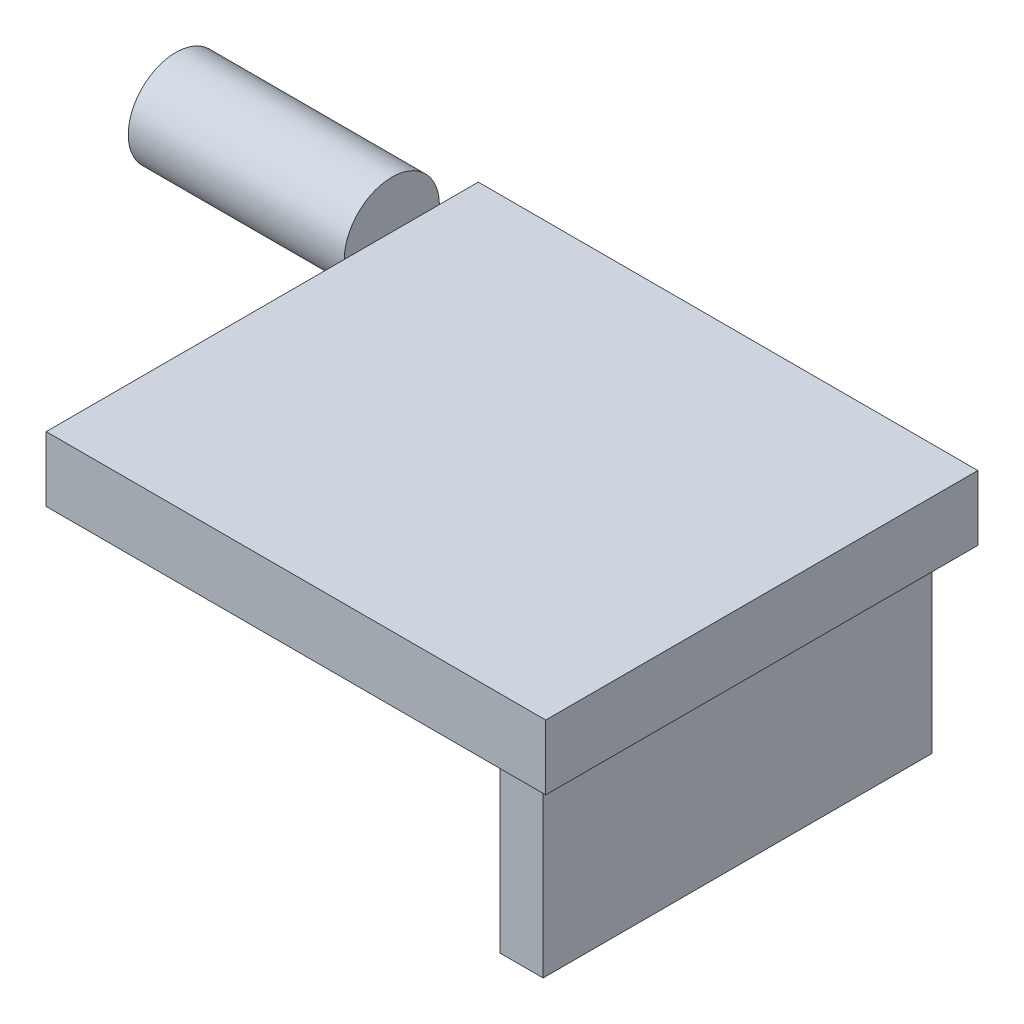
SolidWorks part; units mm, degrees
ref_plane "Front Plane" through (0, 0, 0) normal (0, 0, 1) x (1, 0, 0)
ref_plane "Top Plane" through (0, 0, 0) normal (0, 1, 0) x (1, 0, 0)
ref_plane "Right Plane" through (0, 0, 0) normal (1, 0, 0) x (0, 0, -1)
sketch "Sketch1" plane through (0, 0, 0) normal (0, 1, 0) x (1, 0, 0)
  line L1 (0, 0) -> (29.3624, 0)
  line L2 (0, 0) -> (0, 25.4)
  line L3 (0, 25.4) -> (29.3624, 25.4)
  line L4 (29.3624, 0) -> (29.3624, 25.4)
  dimension "D1" = 25.4
  dimension "D2" = 29.3624
extrude "Boss-Extrude1" add sketch "Sketch1" along normal blind 3.81
sketch "Sketch2" plane through (0, 0, 0) normal (0, -1, 0) x (1, 0, 0)
  line L0 (0, -12.7) -> (29.3624, -12.7) construction
  line L1 (0, -25.4) -> (0, 0) construction
  line L2 (29.3624, 0) -> (29.3624, -25.4) construction
  line L4 (27.94, -24.13) -> (25.4, -24.13)
  line L5 (27.94, -24.13) -> (27.94, -1.27)
  line L6 (27.94, -1.27) -> (25.4, -1.27)
  line L7 (25.4, -24.13) -> (25.4, -1.27)
  line L8 (27.94, -24.13) -> (25.4, -1.27) construction
  line L9 (27.94, -1.27) -> (25.4, -24.13) construction
  point P6 (26.67, -12.7)
  dimension "D1" = 2.54
  dimension "D2" = 22.86
  dimension "D3" = 27.94
extrude "Boss-Extrude2" add sketch "Sketch2" along normal blind 10.668
sketch "Sketch3" plane through (0, 0, 0) normal (-1, 0, 0) x (0, 0, 1)
  line L0 (-25.4, 3.81) -> (0, 3.81) construction
  line L1 (-25.4, 3.81) -> (-25.4, 0) construction
  circle A0 centre (-20.32, 3.81) radius 2.794
  dimension "D1" = 5.588
  dimension "D2" = 5.08
extrude "Boss-Extrude3" add sketch "Sketch3" along normal blind 12.7
